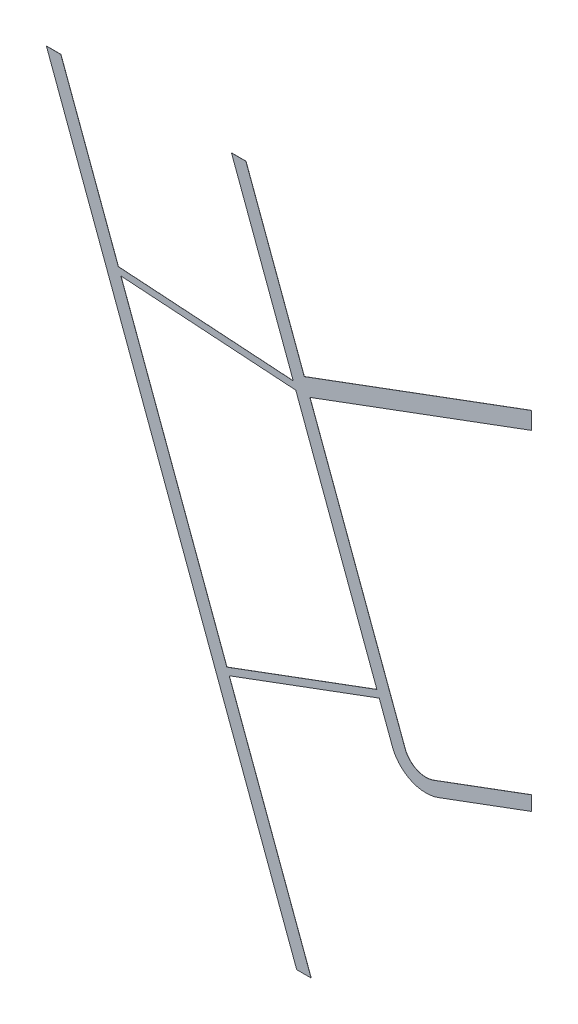
SolidWorks part; units mm, degrees
ref_plane "Front Plane" through (0, 0, 0) normal (0, 0, 1) x (1, 0, 0)
ref_plane "Top Plane" through (0, 0, 0) normal (0, 1, 0) x (1, 0, 0)
ref_plane "Right Plane" through (0, 0, 0) normal (1, 0, 0) x (0, 0, -1)
sketch "Sketch2" plane through (0, 0, 0) normal (0, 0, 1) x (1, 0, 0)
  line L1 (76038.761, -250000) -> (-109445.11, 250000)
  line L2 (86704.6743, -250000) -> (26009.0734, -86385.7714)
  line L5 (146955.4456, -71428.5814) -> (136459.21, -43134.3812)
  line L6 (156331.1078, -67950.5132) -> (85803.0786, 122168.522)
  line L9 (75362.2991, 121561.6396) -> (-54293.7379, 130082.6763)
  line L10 (73507.4604, 126561.6396) -> (-56148.5766, 135082.6763)
  line L12 (-20997.0947, 97829.6926) -> (32833.2448, -47278.1791) construction
  line L13 (-20997.0947, 97829.6926) -> (12180.289, 95649.2642) construction
  line L14 (24270.0393, -81697.9403) -> (24698.3388, -82852.487)
  line L15 (24270.0393, -81697.9403) -> (135462.9978, -40448.9396)
  line L16 (26009.0734, -86385.7714) -> (137202.032, -45136.7707)
  line L17 (136459.21, -43134.3812) -> (137202.032, -45136.7707)
  line L18 (81504.9155, 47500.0976) -> (66452.5436, 88076.0566) construction
  line L19 (250000, 250000) -> (-250000, 250000) construction
  line L21 (81629.3967, 133419.3167) -> (250000, 195879.3792)
  line L22 (85803.0786, 122168.522) -> (250000, 183080.2832)
  line L24 (250000, -250000) -> (250000, 250000) construction
  line L25 (-250000, -250000) -> (250000, -250000) construction
  line L26 (181012.4196, -87054.7224) -> (250000, -61462.5555)
  line L27 (177523.6375, -77674.1445) -> (250000, -50787.7519)
  line L28 (76038.761, -250000) -> (86704.6743, -250000)
  line L29 (250000, -61462.5555) -> (250000, -50787.7519)
  line L30 (27715.8106, 250000) -> (38381.7239, 250000)
  line L31 (250000, 183080.2832) -> (250000, 195879.3792)
  line L32 (-109445.11, 250000) -> (-98779.1967, 250000)
  line L33 (81629.3967, 133419.3167) -> (38381.7239, 250000)
  line L34 (-56148.5766, 135082.6763) -> (-98779.1967, 250000)
  line L35 (73507.4604, 126561.6396) -> (27715.8106, 250000)
  line L36 (24698.3388, -82852.487) -> (-54293.7379, 130082.6763)
  line L37 (135462.9978, -40448.9396) -> (75362.2991, 121561.6396)
  arc A0 (146955.4456, -71428.5814) -> (181012.4196, -87054.7224) centre (171797.0031, -62213.165) ccw
  arc A1 (156331.1078, -67950.5132) -> (177523.6375, -77674.1445) centre (171789.1883, -62216.064) ccw
  point P40 (0, 0)
  dimension "D1" = 10000
  dimension "D2" = 10000
  dimension "D3" = 5000
  dimension "D4" = 20000
  dimension "D5" = 20000
  dimension "D6" = 30000
  dimension "D7" = 5000
  dimension "D8" = 12000
extrude "Boss-Extrude1" add sketch "Sketch2" along normal blind 100 draft 1
